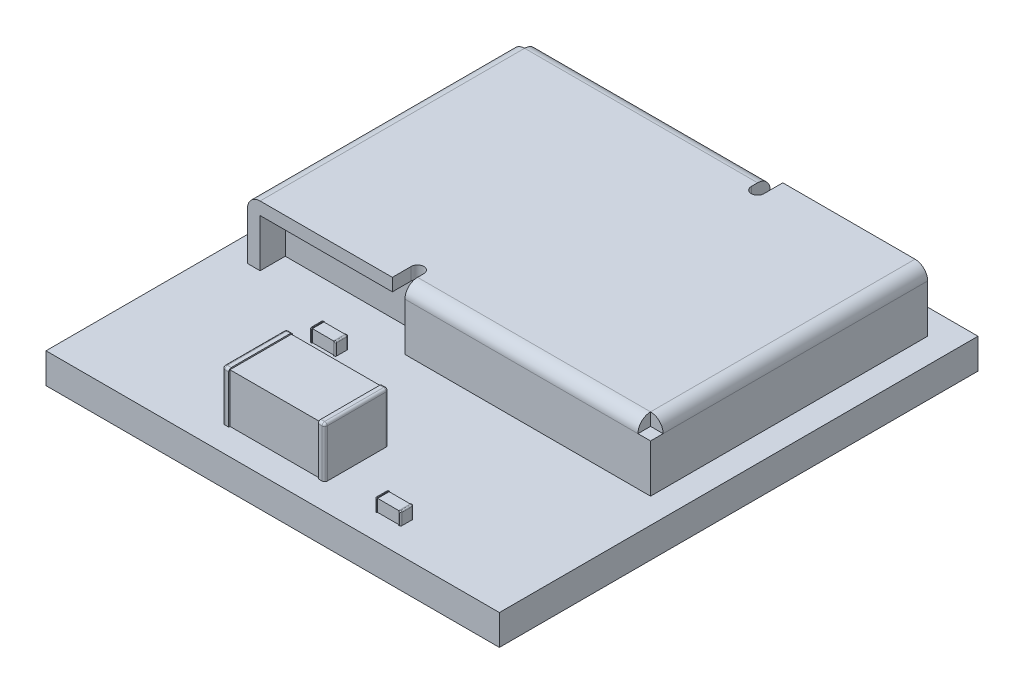
SolidWorks part; units mm, degrees
ref_plane "Front Plane" through (0, 0, 0) normal (0, 0, 1) x (1, 0, 0)
ref_plane "Top Plane" through (0, 0, 0) normal (0, 1, 0) x (1, 0, 0)
ref_plane "Right Plane" through (0, 0, 0) normal (1, 0, 0) x (0, 0, -1)
sketch "Sketch1" plane through (0, 0, 0) normal (0, 1, 0) x (1, 0, 0)
  line L0 (4.5, 4.75) -> (-4.5, -4.75) construction
  line L1 (-4.5, 4.75) -> (4.5, 4.75)
  line L2 (-4.5, 4.75) -> (-4.5, -4.75)
  line L3 (-4.5, -4.75) -> (4.5, -4.75)
  line L4 (4.5, 4.75) -> (4.5, -4.75)
  dimension "D1" = 9
  dimension "D2" = 9.5
extrude "Boss-Extrude1" add sketch "Sketch1" along normal blind 0.6
sketch "Sketch2" plane through (0, 0.6, 0) normal (0, 1, 0) x (1, 0, 0)
  line L0 (-4.5, 4.75) -> (-4.5, -4.75) construction
  line L1 (-4, 4.25) -> (4, 4.25)
  line L2 (-4, 4.25) -> (-4, -1.25)
  line L3 (-4, -1.25) -> (4, -1.25)
  line L4 (4, 4.25) -> (4, -1.25)
  line L5 (4.5, 4.75) -> (-4.5, 4.75) construction
  line L6 (4.5, -4.75) -> (4.5, 4.75) construction
  dimension "D1" = 0.5
  dimension "D2" = 0.5
  dimension "D3" = 0.5
  dimension "D4" = 5.5
extrude "Boss-Extrude2" add sketch "Sketch2" along normal blind 1.2
sketch "Sketch3" plane through (0, 1.8, 0) normal (0, 1, 0) x (1, 0, 0)
  line L0 (0.875, 4.25) -> (0.875, 3.875)
  line L1 (1.125, 4.25) -> (1.125, 3.875)
  line L2 (-1.125, -0.875) -> (-1.125, -1.25)
  line L3 (-0.875, -0.875) -> (-0.875, -1.25)
  line L4 (-1.125, -1.25) -> (-0.875, -1.25)
  line L6 (0.875, 4.25) -> (1.125, 4.25)
  line L8 (-4, -1.25) -> (4, -1.25) construction
  line L9 (4, 4.25) -> (-4, 4.25) construction
  line L10 (-4, 4.25) -> (-4, -1.25) construction
  line L11 (4, -1.25) -> (4, 4.25) construction
  arc A0 (-0.875, -0.875) -> (-1.125, -0.875) centre (-1, -0.875) ccw
  arc A1 (0.875, 3.875) -> (1.125, 3.875) centre (1, 3.875) ccw
  dimension "D1" = 0.25
  dimension "D2" = 0.5
  dimension "D3" = 0.5
  dimension "D4" = 3
  dimension "D5" = 3
extrude "Cut-Extrude1" cut sketch "Sketch3" against normal up to surface (1.2 mm away) up to face at (0, 0.6, 0)
sketch "Sketch4" plane through (0, 1.8, 0) normal (0, 1, 0) x (1, 0, 0)
  line L1 (4, -1.25) -> (3.75, -1.25)
  line L2 (4, -1.25) -> (4, -1)
  line L3 (4, -1) -> (3.75, -1)
  line L4 (3.75, -1.25) -> (3.75, -1)
  line L5 (-4, 4.25) -> (-3.75, 4.25)
  line L6 (-4, 4.25) -> (-4, 4)
  line L7 (-4, 4) -> (-3.75, 4)
  line L8 (-3.75, 4.25) -> (-3.75, 4)
  dimension "D1" = 0.25
extrude "Cut-Extrude2" cut sketch "Sketch4" against normal blind 0.25
fillet "Fillet1" radius 0.25 4 edges at (-1.4375, 1.8, -4.25) (4, 1.8, -1.625) (1.4375, 1.8, 1.25) (-4, 1.8, -1.375)
sketch "Sketch5" plane through (0, 0, 1.25) normal (0, 0, 1) x (1, 0, 0)
  line L0 (-3.75, 1.8) -> (-1.125, 1.8) construction
  line L1 (-0.875, 0.6) -> (-3.75, 0.6)
  line L2 (-0.875, 0.6) -> (-0.875, 1.55)
  line L3 (-0.875, 1.55) -> (-3.75, 1.55)
  line L4 (-3.75, 0.6) -> (-3.75, 1.55)
  line L5 (-4, 1.55) -> (-4, 0.6) construction
  line L6 (-0.875, 0.6) -> (4, 0.6) construction
  line L7 (-0.875, 0.6) -> (-0.875, 1.55) construction
  dimension "D1" = 0.25
  dimension "D2" = 0.25
extrude "Cut-Extrude3" cut sketch "Sketch5" against normal blind 0.5
sketch "Sketch7" plane through (0, 0, -4.25) normal (0, 0, -1) x (-1, 0, 0)
  line L0 (-3.75, 1.8) -> (-1.125, 1.8) construction
  line L1 (-0.875, 0.6) -> (-3.75, 0.6)
  line L2 (-0.875, 0.6) -> (-0.875, 1.55)
  line L3 (-0.875, 1.55) -> (-3.75, 1.55)
  line L4 (-3.75, 0.6) -> (-3.75, 1.55)
  line L5 (-4, 1.55) -> (-4, 0.6) construction
  dimension "D1" = 0.25
  dimension "D2" = 0.25
extrude "Cut-Extrude4" cut sketch "Sketch7" against normal blind 0.5
sketch "Sketch8" plane through (0, 0.6, 0) normal (0, 1, 0) x (1, 0, 0)
  line L0 (-4.5, 4.75) -> (-4.5, -4.75) construction
  line L1 (-1.5, -2.98) -> (-1.373, -2.98)
  line L2 (-1.5, -2.98) -> (-1.5, -4.25)
  line L3 (-1.5, -4.25) -> (-1.373, -4.25)
  line L4 (0.532, -2.98) -> (0.532, -4.25)
  line L5 (-4.5, -4.75) -> (4.5, -4.75) construction
  line L6 (-1.373, -4.25) -> (-1.373, -4.2246)
  line L7 (-1.373, -4.2246) -> (0.405, -4.2246)
  line L8 (0.405, -4.2246) -> (0.405, -4.25)
  line L9 (0.405, -2.98) -> (0.405, -3.0054)
  line L10 (0.405, -3.0054) -> (-1.373, -3.0054)
  line L11 (-1.373, -3.0054) -> (-1.373, -2.98)
  line L12 (0.405, -2.98) -> (0.532, -2.98)
  line L13 (0.405, -4.25) -> (0.532, -4.25)
  dimension "D1" = 3
  dimension "D2" = 0.5
  dimension "D3" = 1.27
  dimension "D4" = 2.032
  dimension "D5" = 0.127
  dimension "D6" = 0.127
  dimension "D7" = 0.0254
extrude "Boss-Extrude3" add sketch "Sketch8" along normal blind 1
sketch "Sketch9" plane through (0, 1.6, 0) normal (0, 1, 0) x (1, 0, 0)
  line L1 (-1.373, -3.0054) -> (0.405, -3.0054)
  line L2 (-1.373, -3.0054) -> (-1.373, -4.2246)
  line L3 (-1.373, -4.2246) -> (0.405, -4.2246)
  line L4 (0.405, -3.0054) -> (0.405, -4.2246)
extrude "Cut-Extrude5" cut sketch "Sketch9" against normal blind 0.0254
fillet "Fillet2" radius 0.0508 10 edges at (-1.5, 1.1, 2.98) (0.532, 1.1, 2.98) (0.532, 1.6, 3.615) (0.532, 1.1, 4.25) (-1.5, 1.6, 3.615) (-1.5, 1.1, 4.25) (-1.4365, 1.6, 2.98) (0.4685, 1.6, 2.98) (0.4685, 1.6, 4.25) (-1.4365, 1.6, 4.25)
sketch "Sketch10" plane through (0, 0.6, 0) normal (0, 1, 0) x (1, 0, 0)
  line L0 (0.405, -4.25) -> (0.4812, -4.25) construction
  line L1 (-2.033, -1.726) -> (-1.9949, -1.726)
  line L2 (-2.033, -1.726) -> (-2.033, -1.98)
  line L3 (-2.033, -1.98) -> (-1.9949, -1.98)
  line L4 (-1.525, -1.726) -> (-1.525, -1.98)
  line L5 (1.532, -3.996) -> (1.5701, -3.996)
  line L6 (1.532, -3.996) -> (1.532, -4.25)
  line L7 (1.532, -4.25) -> (1.5701, -4.25)
  line L8 (2.04, -3.996) -> (2.04, -4.25)
  line L9 (-1.5, -3.0308) -> (-1.5, -4.1992) construction
  line L10 (0.532, -3.0308) -> (0.532, -4.1992) construction
  line L11 (-1.4492, -2.98) -> (-1.373, -2.98) construction
  line L12 (-1.9949, -1.9673) -> (-1.5631, -1.9673)
  line L13 (-1.9949, -1.7387) -> (-1.5631, -1.7387)
  line L14 (-1.5631, -1.726) -> (-1.5631, -1.7387)
  line L15 (-1.9949, -1.726) -> (-1.9949, -1.7387)
  line L16 (1.5701, -3.996) -> (1.5701, -4.0087)
  line L17 (2.0019, -3.996) -> (2.0019, -4.0087)
  line L18 (1.5701, -4.0087) -> (2.0019, -4.0087)
  line L19 (1.5701, -4.2373) -> (2.0019, -4.2373)
  line L20 (1.5701, -4.2373) -> (1.5701, -4.25)
  line L21 (2.0019, -4.2373) -> (2.0019, -4.25)
  line L22 (2.0019, -3.996) -> (2.04, -3.996)
  line L23 (2.0019, -4.25) -> (2.04, -4.25)
  line L24 (-1.9949, -1.9673) -> (-1.9949, -1.98)
  line L25 (-1.5631, -1.9673) -> (-1.5631, -1.98)
  line L26 (-1.5631, -1.98) -> (-1.525, -1.98)
  line L27 (-1.5631, -1.726) -> (-1.525, -1.726)
  dimension "D1" = 0.025
  dimension "D2" = 1
  dimension "D3" = 0.254
  dimension "D4" = 0.508
  dimension "D5" = 1
  dimension "D6" = 0.508
  dimension "D7" = 0.0127
  dimension "D8" = 0.0381
extrude "Boss-Extrude4" add sketch "Sketch10" along normal blind 0.254
sketch "Sketch11" plane through (0, 0.854, 0) normal (0, 1, 0) x (1, 0, 0)
  line L0 (1.5701, -4.2373) -> (2.0019, -4.2373) construction
  line L1 (-1.9949, -1.7387) -> (-1.5631, -1.7387)
  line L2 (-1.9949, -1.7387) -> (-1.9949, -1.9673)
  line L3 (-1.9949, -1.9673) -> (-1.5631, -1.9673)
  line L4 (-1.5631, -1.7387) -> (-1.5631, -1.9673)
  line L5 (1.5701, -4.0087) -> (2.0019, -4.0087)
  line L6 (1.5701, -4.0087) -> (1.5701, -4.2373)
  line L7 (1.5701, -4.2373) -> (2.0019, -4.2373)
  line L8 (2.0019, -4.0087) -> (2.0019, -4.2373)
extrude "Cut-Extrude6" cut sketch "Sketch11" against normal blind 0.0127
fillet "Fillet3" radius 0.0254 20 edges at (-2.033, 0.727, 1.726) (-2.0139, 0.854, 1.726) (-1.525, 0.727, 1.726) (-1.5441, 0.854, 1.726) (-1.525, 0.854, 1.853) (-1.525, 0.727, 1.98) (-1.5441, 0.854, 1.98) (-2.033, 0.854, 1.853) (-2.0139, 0.854, 1.98) (-2.033, 0.727, 1.98) (2.04, 0.727, 3.996) (2.04, 0.854, 4.123) (2.04, 0.727, 4.25) (2.0209, 0.854, 4.25) (2.0209, 0.854, 3.996) (1.532, 0.727, 3.996) (1.551, 0.854, 3.996) (1.532, 0.854, 4.123) (1.551, 0.854, 4.25) (1.532, 0.727, 4.25)
